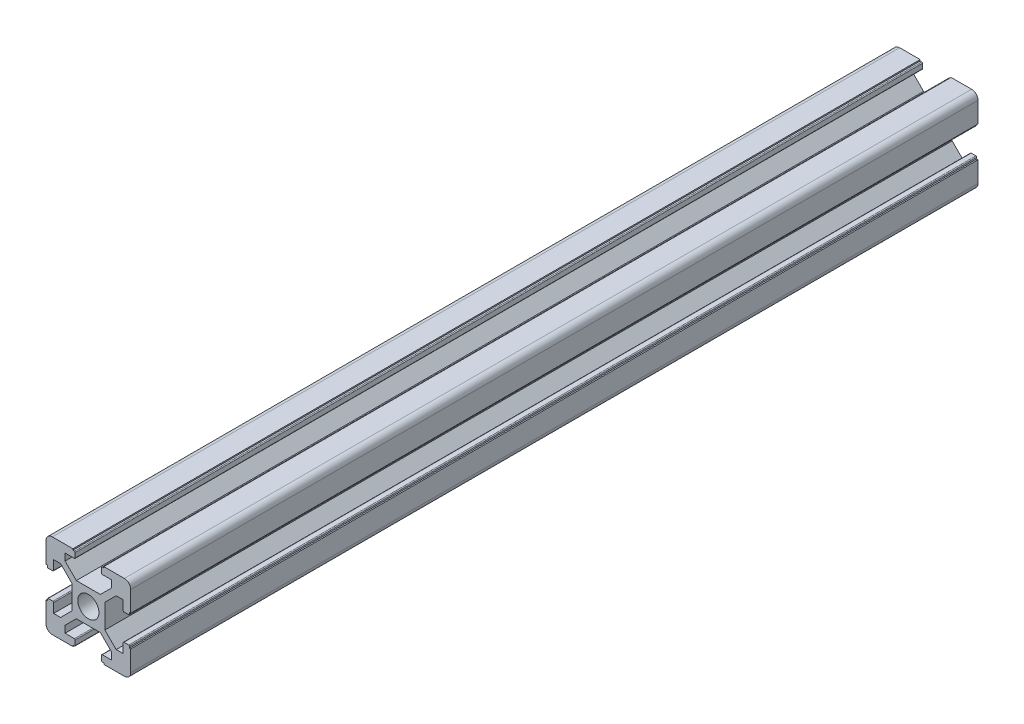
SolidWorks part; units mm, degrees
ref_plane "前视基准面" through (0, 0, 0) normal (0, 0, 1) x (1, 0, 0)
ref_plane "上视基准面" through (0, 0, 0) normal (0, 1, 0) x (1, 0, 0)
ref_plane "右视基准面" through (0, 0, 0) normal (1, 0, 0) x (0, 0, -1)
sketch "草图1" plane through (0, 0, 0) normal (0, 0, 1) x (1, 0, 0)
  line L0 (-17.5, 0) -> (33.5, 0) construction
  line L1 (0, 35.5833) -> (0, -31.0833) construction
  line L2 (3.65, 10) -> (8.5, 10)
  line L3 (10, 10) -> (10, -10) construction
  line L4 (-2.8393, 3.9) -> (2.8393, 3.9)
  line L5 (3.9, 2.8393) -> (3.9, -2.8393)
  line L6 (5.5, 8.2) -> (5.5, 6.5607)
  line L7 (3.9, 3.9) -> (10, 10) construction
  line L8 (4.4303, 3.3697) -> (6.5607, 5.5) construction
  line L9 (3.65, 10) -> (3.65, 8.2)
  line L10 (3.65, 8.2) -> (5.5, 8.2)
  line L11 (3.3697, 4.4303) -> (5.5, 6.5607) construction
  line L12 (5.5, 6.5607) -> (2.8393, 3.9)
  line L13 (6.5607, 5.5) -> (3.9, 2.8393)
  line L14 (3.3697, 4.4303) -> (9.4697, 10.5303) construction
  line L15 (4.4303, 3.3697) -> (10.5303, 9.4697) construction
  line L16 (8.2, 5.5) -> (6.5607, 5.5)
  line L17 (8.2, 3.65) -> (8.2, 5.5)
  line L18 (10, 3.65) -> (10, 8.5)
  line L19 (10, 3.65) -> (8.2, 3.65)
  line L20 (-3.3697, 4.4303) -> (-5.5, 6.5607) construction
  line L21 (-4.4303, 3.3697) -> (-6.5607, 5.5) construction
  line L22 (-3.9, 3.9) -> (-10, 10) construction
  line L23 (-10, 10) -> (-10, -10) construction
  line L24 (-10, 3.65) -> (-8.2, 3.65)
  line L25 (-10, 3.65) -> (-10, 8.5)
  line L26 (-8.2, 3.65) -> (-8.2, 5.5)
  line L27 (-8.2, 5.5) -> (-6.5607, 5.5)
  line L28 (-6.5607, 5.5) -> (-3.9, 2.8393)
  line L29 (-5.5, 6.5607) -> (-2.8393, 3.9)
  line L30 (-3.65, 8.2) -> (-5.5, 8.2)
  line L31 (-3.65, 10) -> (-3.65, 8.2)
  line L32 (-5.5, 8.2) -> (-5.5, 6.5607)
  line L33 (-3.9, 2.8393) -> (-3.9, -2.8393)
  line L34 (-3.65, 10) -> (-8.5, 10)
  line L35 (-3.9, -3.9) -> (-10, -10) construction
  line L36 (-4.4303, -3.3697) -> (-6.5607, -5.5) construction
  line L37 (-3.3697, -4.4303) -> (-5.5, -6.5607) construction
  line L38 (3.3697, -4.4303) -> (5.5, -6.5607) construction
  line L39 (4.4303, -3.3697) -> (6.5607, -5.5) construction
  line L40 (3.9, -3.9) -> (10, -10) construction
  line L41 (-3.65, -10) -> (-8.5, -10)
  line L42 (-5.5, -8.2) -> (-5.5, -6.5607)
  line L43 (-3.65, -10) -> (-3.65, -8.2)
  line L44 (-3.65, -8.2) -> (-5.5, -8.2)
  line L45 (-5.5, -6.5607) -> (-2.8393, -3.9)
  line L46 (-6.5607, -5.5) -> (-3.9, -2.8393)
  line L47 (-8.2, -5.5) -> (-6.5607, -5.5)
  line L48 (-8.2, -3.65) -> (-8.2, -5.5)
  line L49 (-10, -3.65) -> (-10, -8.5)
  line L50 (-10, -3.65) -> (-8.2, -3.65)
  line L51 (10, -3.65) -> (8.2, -3.65)
  line L52 (10, -3.65) -> (10, -8.5)
  line L53 (8.2, -3.65) -> (8.2, -5.5)
  line L54 (8.2, -5.5) -> (6.5607, -5.5)
  line L55 (6.5607, -5.5) -> (3.9, -2.8393)
  line L56 (5.5, -6.5607) -> (2.8393, -3.9)
  line L57 (3.65, -8.2) -> (5.5, -8.2)
  line L58 (3.65, -10) -> (3.65, -8.2)
  line L59 (5.5, -8.2) -> (5.5, -6.5607)
  line L60 (-2.8393, -3.9) -> (2.8393, -3.9)
  line L61 (3.65, -10) -> (8.5, -10)
  circle A0 centre (0, 0) radius 2.5
  arc A1 (-8.5, -10) -> (-10, -8.5) centre (-8.5, -8.5) cw
  arc A2 (10, -8.5) -> (8.5, -10) centre (8.5, -8.5) cw
  arc A3 (8.5, 10) -> (10, 8.5) centre (8.5, 8.5) cw
  arc A4 (-10, 8.5) -> (-8.5, 10) centre (-8.5, 8.5) cw
  point P13 (0, -3.9)
  point P42 (0, 3.9)
  point P43 (-10, 0)
  point P54 (10, 0)
  point P56 (-3.9, 0)
  point P70 (3.9, 0)
  dimension "D3" = 5
  dimension "D10" = 1.5
  dimension "D1" = 7.3
  dimension "D2" = 10
  dimension "D4" = 3.9
  dimension "D5" = 3.9
  dimension "D8" = 1.8
  dimension "D9" = 0.75
  dimension "D6" = 11
  dimension "D7" = 10
  dimension "D11" = 45
  dimension "D12" = 2.8393
extrude "凸台-拉伸2" add sketch "草图1" along normal blind 200 contours L34 A4 L25 L24 L26 L27 L28 L33 L46 L47 L48 L50 L49 A1 L41 L43 L44 L42 L45 L60 L56 L59 L57 L58 L61 A2 L52 L51 L53 L54 L55 L5 L13 L16 L17 L19 L18 A3 L2 L9 L10 L6 L12 L4 L29 L32 L30 L31
sketch "草图3" plane through (0, 0, 200) normal (0, 0, 1) x (1, 0, 0)
  line L0 (-12.6954, 0) -> (11.5012, 0) construction
  line L1 (0, 10.0863) -> (0, -11.0469) construction
  line L2 (-3.65, 8.2) -> (-3.3, 8.2)
  line L3 (3.65, 8.2) -> (3.6528, 8.2568)
  line L4 (-3.1, 8.4) -> (-3.1, 9.5)
  line L5 (3.65, 9.7) -> (3.65, 8.2)
  line L6 (-3.3, 9.7) -> (-3.65, 9.7)
  line L7 (-3.65, 8.2) -> (-3.65, 10) construction
  line L8 (-3.65, 9.7) -> (-3.65, 8.2)
  line L9 (-3.65, 8.2) -> (-3.6528, 8.2568)
  line L10 (3.3, 9.7) -> (3.65, 9.7)
  line L11 (3.1, 8.4) -> (3.1, 9.5)
  line L12 (3.65, 8.2) -> (3.3, 8.2)
  line L13 (3.65, -8.2) -> (3.3, -8.2)
  line L14 (3.1, -8.4) -> (3.1, -9.5)
  line L15 (3.3, -9.7) -> (3.65, -9.7)
  line L16 (-3.65, -8.2) -> (-3.6528, -8.2568)
  line L17 (-3.65, -9.7) -> (-3.65, -8.2)
  line L18 (-3.3, -9.7) -> (-3.65, -9.7)
  line L19 (3.65, -9.7) -> (3.65, -8.2)
  line L20 (-3.1, -8.4) -> (-3.1, -9.5)
  line L21 (3.65, -8.2) -> (3.6528, -8.2568)
  line L22 (-3.65, -8.2) -> (-3.3, -8.2)
  line L23 (0, 0) -> (9.5607, 9.5607) construction
  line L24 (-8.2, -3.65) -> (-8.2, -3.3)
  line L25 (-8.4, -3.1) -> (-9.5, -3.1)
  line L26 (-9.7, -3.3) -> (-9.7, -3.65)
  line L27 (-9.7, -3.65) -> (-8.2, -3.65)
  line L28 (-8.2, -3.65) -> (-8.2568, -3.6528)
  line L29 (8.2, 3.65) -> (8.2, 3.3)
  line L30 (8.4, 3.1) -> (9.5, 3.1)
  line L31 (9.7, 3.3) -> (9.7, 3.65)
  line L32 (9.7, 3.65) -> (8.2, 3.65)
  line L33 (8.2, 3.65) -> (8.2568, 3.6528)
  line L34 (-8.2, 3.65) -> (-8.2568, 3.6528)
  line L35 (-9.7, 3.65) -> (-8.2, 3.65)
  line L36 (-9.7, 3.3) -> (-9.7, 3.65)
  line L37 (-8.4, 3.1) -> (-9.5, 3.1)
  line L38 (-8.2, 3.65) -> (-8.2, 3.3)
  line L39 (8.2, -3.65) -> (8.2568, -3.6528)
  line L40 (9.7, -3.65) -> (8.2, -3.65)
  line L41 (9.7, -3.3) -> (9.7, -3.65)
  line L42 (8.4, -3.1) -> (9.5, -3.1)
  line L43 (8.2, -3.65) -> (8.2, -3.3)
  arc A0 (-3.1, 9.5) -> (-3.3, 9.7) centre (-3.3, 9.5) ccw
  arc A1 (-3.3, 8.2) -> (-3.1, 8.4) centre (-3.3, 8.4) ccw
  arc A2 (3.3, 8.2) -> (3.1, 8.4) centre (3.3, 8.4) cw
  arc A3 (3.1, 9.5) -> (3.3, 9.7) centre (3.3, 9.5) cw
  arc A4 (3.1, -9.5) -> (3.3, -9.7) centre (3.3, -9.5) ccw
  arc A5 (3.3, -8.2) -> (3.1, -8.4) centre (3.3, -8.4) ccw
  arc A6 (-3.3, -8.2) -> (-3.1, -8.4) centre (-3.3, -8.4) cw
  arc A7 (-3.1, -9.5) -> (-3.3, -9.7) centre (-3.3, -9.5) cw
  arc A8 (10, 8.5) -> (8.5, 10) centre (8.5, 8.5) ccw construction
  arc A9 (-9.5, -3.1) -> (-9.7, -3.3) centre (-9.5, -3.3) ccw
  arc A10 (-8.2, -3.3) -> (-8.4, -3.1) centre (-8.4, -3.3) ccw
  arc A11 (9.5, 3.1) -> (9.7, 3.3) centre (9.5, 3.3) ccw
  arc A12 (8.2, 3.3) -> (8.4, 3.1) centre (8.4, 3.3) ccw
  arc A13 (-8.2, 3.3) -> (-8.4, 3.1) centre (-8.4, 3.3) cw
  arc A14 (-9.5, 3.1) -> (-9.7, 3.3) centre (-9.5, 3.3) cw
  arc A15 (8.2, -3.3) -> (8.4, -3.1) centre (8.4, -3.3) cw
  arc A16 (9.5, -3.1) -> (9.7, -3.3) centre (9.5, -3.3) cw
  point P16 (-3.1, 9.7)
  point P19 (-3.1, 8.2)
  point P29 (3.1, 8.2)
  point P30 (3.1, 9.7)
  point P49 (3.1, -9.7)
  point P50 (3.1, -8.2)
  point P51 (-3.1, -8.2)
  point P52 (-3.1, -9.7)
  point P67 (-9.7, -3.1)
  point P68 (-8.2, -3.1)
  point P78 (9.7, 3.1)
  point P79 (8.2, 3.1)
  point P89 (-8.2, 3.1)
  point P90 (-9.7, 3.1)
  point P100 (8.2, -3.1)
  point P101 (9.7, -3.1)
  line M1 (-3.65, -10) -> (-3.65, -8.2)
  line M9 (3.65, -8.2) -> (3.65, -10)
  line M21 (8.2, 3.65) -> (10, 3.65)
  line M25 (3.65, 10) -> (3.65, 8.2)
  line M33 (-3.65, 8.2) -> (-3.65, 10)
  line M37 (-10, 3.65) -> (-8.2, 3.65)
  dimension "D3" = 0.2
  dimension "D1" = 6.2
  dimension "D2" = 1.5
extrude "凸台-拉伸3" add sketch "草图3" against normal blind 200 contours A14 L37 A13 L38 L36 M37 | L2 A1 L4 A0 L6 M33 | A3 L11 A2 L12 L10 M25 | L29 A12 L30 A11 L31 M21 | L13 A5 L14 A4 L15 M9 | A7 L20 A6 L22 L18 M1 | L43 A15 L42 A16 L41 L40 | L24 A10 L25 A9 L26 L27
